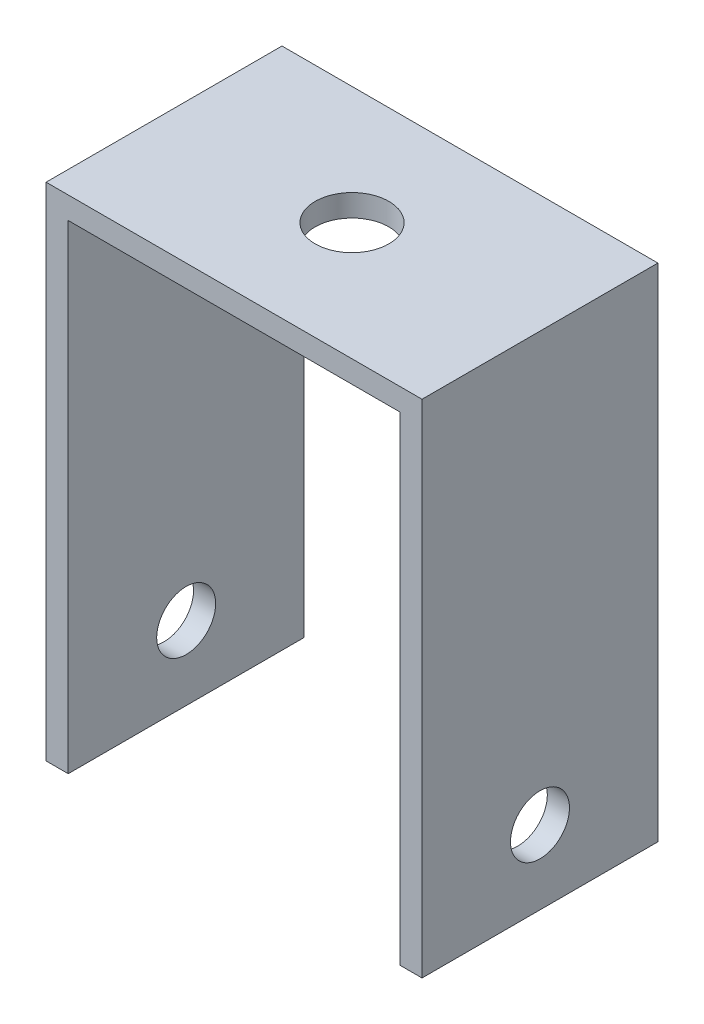
SolidWorks part; units mm, degrees
ref_plane "Front Plane" through (0, 0, 0) normal (0, 0, 1) x (1, 0, 0)
ref_plane "Top Plane" through (0, 0, 0) normal (0, 1, 0) x (1, 0, 0)
ref_plane "Right Plane" through (0, 0, 0) normal (1, 0, 0) x (0, 0, -1)
sketch "Sketch1" plane through (0, 0, 0) normal (0, 0, 1) x (1, 0, 0)
  line L0 (-22.5, 0) -> (-22.5, 65)
  line L1 (-22.5, 65) -> (22.5, 65)
  line L2 (-22.5, 0) -> (-25.5, 0)
  line L3 (-25.5, 0) -> (-25.5, 68)
  line L4 (-25.5, 68) -> (25.5, 68)
  line L5 (0, -55) -> (0, 55) construction
  line L6 (22.5, 0) -> (25.5, 0)
  line L7 (22.5, 0) -> (22.5, 65)
  line L8 (25.5, 0) -> (25.5, 68)
  point P12 (0, 65)
  point P13 (0, 68)
  dimension "D1" = 22.5
extrude "Boss-Extrude1" add sketch "Sketch1" along normal mid plane 32
sketch "Sketch2" plane through (25.5, 0, 0) normal (1, 0, 0) x (0, 0, -1)
  circle A0 centre (0, 10) radius 4
  dimension "D1" = 10
extrude "Cut-Extrude1" cut sketch "Sketch2" against normal through all
sketch "Sketch3" plane through (0, 68, 0) normal (0, 1, 0) x (1, 0, 0)
  circle A0 centre (0, 0) radius 5
extrude "Cut-Extrude2" cut sketch "Sketch3" against normal blind 32
